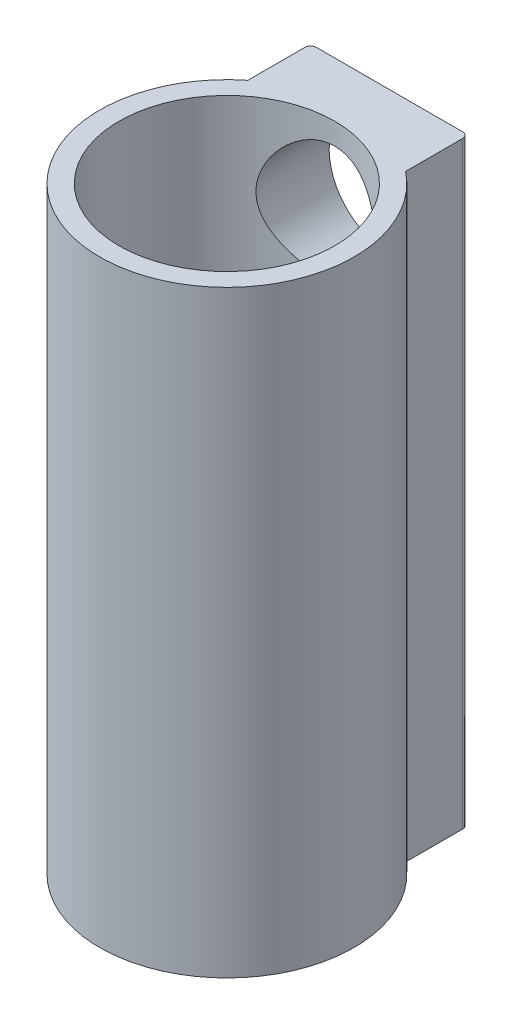
SolidWorks part; units mm, degrees
ref_plane "Front Plane" through (0, 0, 0) normal (0, 0, 1) x (1, 0, 0)
ref_plane "Top Plane" through (0, 0, 0) normal (0, 1, 0) x (1, 0, 0)
ref_plane "Right Plane" through (0, 0, 0) normal (1, 0, 0) x (0, 0, -1)
sketch "Sketch1" plane through (0, 0, 0) normal (0, 1, 0) x (1, 0, 0)
  line L6 (2.45, 3.0984) -> (2.45, 5.05)
  line L7 (2.45, 5.05) -> (-2.45, 5.05)
  line L8 (-2.45, 3.0984) -> (-2.45, 5.05)
  line L9 (2.45, 3.0984) -> (-2.45, 5.05) construction
  line L10 (2.45, 5.05) -> (-2.45, 3.0984) construction
  arc A1 (-2.45, 3.0984) -> (2.45, 3.0984) centre (0, 0) ccw
  point P2 (0, 4.0742)
  point P9 (0, -3.95)
  dimension "D3" = 9
  dimension "D2" = 4.9
extrude "Boss-Extrude1" add sketch "Sketch1" along normal blind 18.57
sketch "Sketch2" plane through (0, 0, 0) normal (0, -1, 0) x (1, 0, 0)
  circle A0 centre (0, 0) radius 3.35
  arc A1 (2.45, -3.0984) -> (-2.45, -3.0984) centre (0, 0) ccw construction
  dimension "D1" = 0.6
extrude "Cut-Extrude1" cut sketch "Sketch2" against normal blind 18.57
sketch "Sketch3" plane through (0, 0, -5.05) normal (0, 0, -1) x (-1, 0, 0)
  circle A0 centre (0, 16.025) radius 1.875
  circle A1 centre (0, 3.075) radius 1.875
  point P4 (0, 17.9)
  point P6 (0, 14.15)
  point P7 (0, 4.95)
  point P9 (0, 1.2)
  dimension "D1" = 3.75
  dimension "D2" = 3.75
  dimension "D3" = 9.2
  dimension "D4" = 1.2
extrude "Cut-Extrude2" cut sketch "Sketch3" against normal up to surface (2.2739 mm away)
fillet "Fillet1" radius 0.18 2 edges at (2.45, 9.285, -5.05) (-2.45, 9.285, -5.05)
